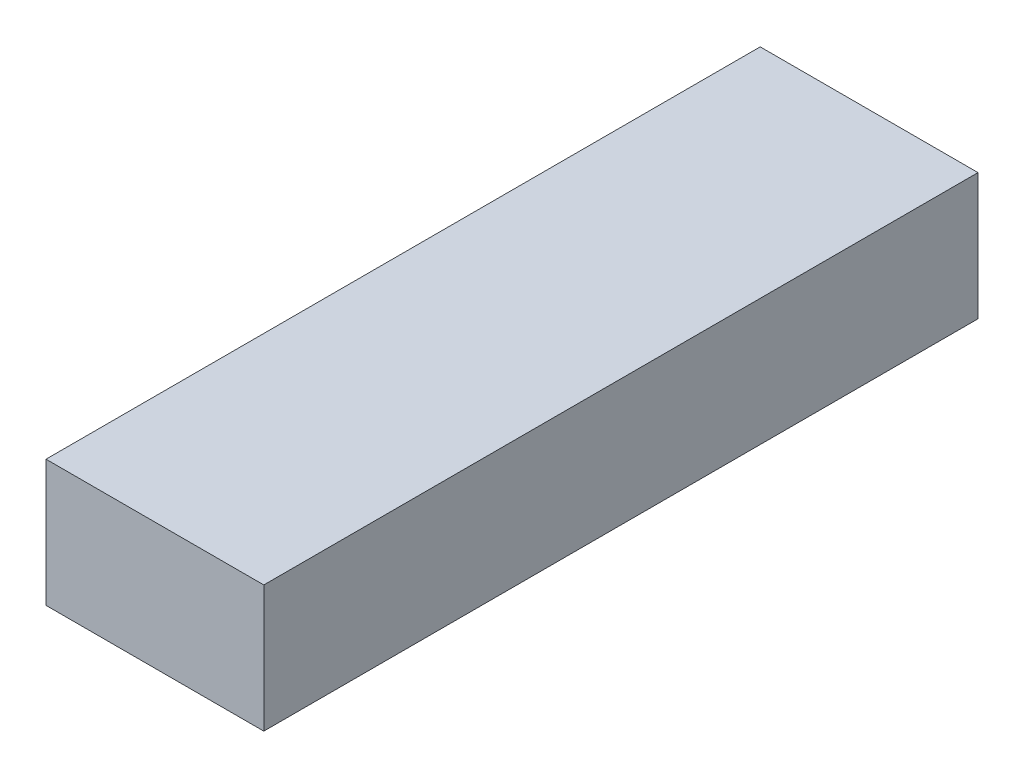
SolidWorks part; units mm, degrees
material "Tungsten"
ref_plane "Front Plane" through (0, 0, 0) normal (0, 0, 1) x (1, 0, 0)
ref_plane "Top Plane" through (0, 0, 0) normal (0, 1, 0) x (1, 0, 0)
ref_plane "Right Plane" through (0, 0, 0) normal (1, 0, 0) x (0, 0, -1)
sketch "Sketch1" plane through (0, 0, 0) normal (0, 0, 1) x (1, 0, 0)
  line L1 (-21.5, -12.5) -> (21.5, -12.5)
  line L2 (-21.5, -12.5) -> (-21.5, 12.5)
  line L3 (-21.5, 12.5) -> (21.5, 12.5)
  line L4 (21.5, -12.5) -> (21.5, 12.5)
  line L5 (-21.5, -12.5) -> (21.5, 12.5) construction
  line L6 (-21.5, 12.5) -> (21.5, -12.5) construction
  point P0 (0, 0)
extrude "Boss-Extrude1" add sketch "Sketch1" along normal blind 141
